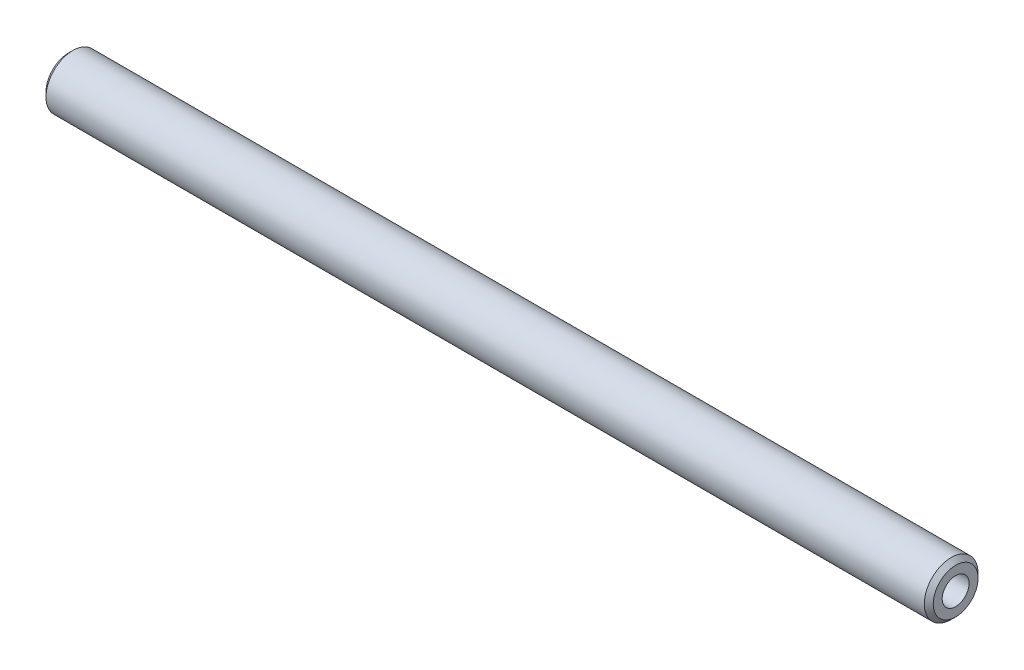
SolidWorks part; units mm, degrees
material "1.4301 (X5CrNi18-10)"
ref_plane "正面" through (0, 0, 0) normal (0, 0, 1) x (1, 0, 0)
ref_plane "平面" through (0, 0, 0) normal (0, 1, 0) x (1, 0, 0)
ref_plane "右側面" through (0, 0, 0) normal (1, 0, 0) x (0, 0, -1)
sketch "ｽｹｯﾁ1" plane through (0, 0, 0) normal (0, 0, 1) x (1, 0, 0)
  line L0 (0, 0) -> (67520.4334, 0) construction
  line L2 (-49.5, 0) -> (49.5, 0)
  line L3 (-49.5, 0) -> (-49.5, 3)
  line L4 (-49.5, 3) -> (49.5, 3)
  line L5 (49.5, 0) -> (49.5, 3)
  point P7 (0, 0)
  dimension "D1" = 99
  dimension "D2" = 6
revolve "回転1" add sketch "ｽｹｯﾁ1" angle 360 about L0
chamfer "面取り1" distance 0.5 angle 45 2 edges at (49.5, 0, 3) (-49.5, 0, 3)
hole_wizard "M3x0.5 ねじ穴1" positions "3Dｽｹｯﾁ1" profile "ｽｹｯﾁ2" tap size "M3x0.5" standard "JIS"
sketch3d "3Dｽｹｯﾁ1"
  point P0 (49.5, 0, 0)
  point P3 (-49.5, 0, 0)
sketch "ｽｹｯﾁ2" plane through (49.5, 0, 0) normal (0, 1, 0) x (0, 0, -1)
  line L0 (0, 0) -> (0, 9.2511)
  line L1 (0, 9.2511) -> (1.25, 8.5)
  line L2 (1.25, 8.5) -> (1.25, 6)
  line L3 (1.25, 6) -> (1.5, 6)
  line L4 (1.5, 6) -> (1.5, 0)
  line L5 (1.5, 0) -> (0, 0)
  line L10 (0, 9.2511) -> (-1.25, 8.5) construction
  line L11 (0, -6.35) -> (0, 107.95) construction
  dimension "ねじ下穴ﾄﾞﾘﾙ直径" = 2.5
  dimension "ねじ下穴ﾄﾞﾘﾙの深さ" = 8.5
  dimension "ねじ山の主要直径" = 3
  dimension "ねじ山の深さ" = 6
  dimension "ﾄﾞﾘﾙ角度" = 118
